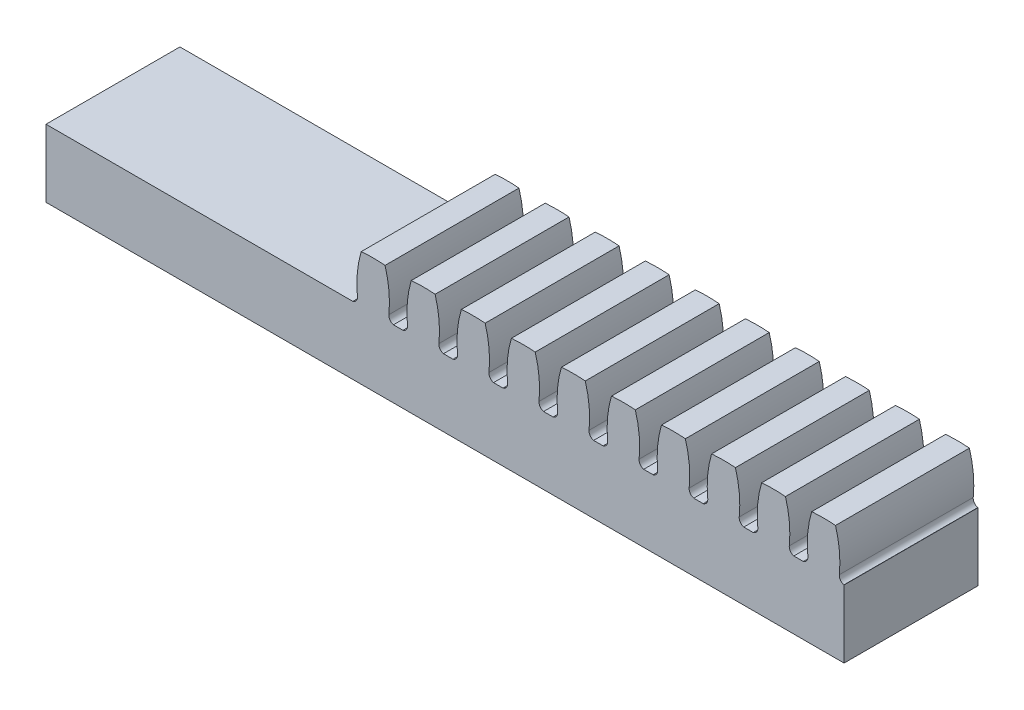
SolidWorks part; units mm, degrees
ref_plane "Front Plane" through (0, 0, 0) normal (0, 0, 1) x (1, 0, 0)
ref_plane "Top Plane" through (0, 0, 0) normal (0, 1, 0) x (1, 0, 0)
ref_plane "Right Plane" through (0, 0, 0) normal (1, 0, 0) x (0, 0, -1)
sketch "Sketch1" plane through (0, 0, 0) normal (0, 1, 0) x (1, 0, 0)
  line L1 (-29.5, 4.545) -> (29.5, 4.545)
  line L2 (-29.5, 4.545) -> (-29.5, -5.355)
  line L3 (-29.5, -5.355) -> (29.5, -5.355)
  line L4 (29.5, 4.545) -> (29.5, -5.355)
  dimension "D1" = 59
  dimension "D2" = 9.9
  dimension "D3" = 4.545
  dimension "D4" = 29.5
extrude "Boss-Extrude1" add sketch "Sketch1" along normal blind 5
sketch "Sketch7" plane through (0, 0, 5.355) normal (0, 0, 1) x (1, 0, 0)
  line L1 (26.47, 4.9959) -> (29.5, 4.9959)
  line L2 (7.97, 4.9959) -> (11, 4.9959)
  line L4 (22.77, 4.9959) -> (25.8, 4.9959)
  line L5 (19.07, 4.9959) -> (22.1, 4.9959)
  line L6 (15.37, 4.9959) -> (18.4, 4.9959)
  line L7 (11.67, 4.9959) -> (14.7, 4.9959)
  line L13 (4.27, 4.9959) -> (7.3, 4.9959)
  line L14 (0.57, 4.9959) -> (3.6, 4.9959)
  line L15 (-3.13, 4.9959) -> (-0.1, 4.9959)
  line L16 (-6.83, 4.9959) -> (-3.8, 4.9959)
  arc A0 (10.6481, 5.4819) -> (11, 4.9959) centre (11.0957, 5.4356) ccw
  arc A1 (7.97, 4.9959) -> (8.3219, 5.4819) centre (7.8743, 5.4356) ccw
  arc A2 (8.6039, 8.4968) -> (8.3219, 5.4819) centre (16.0413, 6.2805) ccw
  arc A3 (10.3661, 8.4968) -> (8.6039, 8.4968) centre (9.485, -1.9662) ccw
  arc A4 (10.6481, 5.4819) -> (10.3661, 8.4968) centre (2.9287, 6.2805) ccw
  arc A5 (29.1481, 5.4819) -> (29.5, 4.9959) centre (29.5957, 5.4356) ccw
  arc A6 (29.1481, 5.4819) -> (28.8661, 8.4968) centre (21.4287, 6.2805) ccw
  arc A7 (28.8661, 8.4968) -> (27.1039, 8.4968) centre (27.985, -1.9662) ccw
  arc A8 (27.1039, 8.4968) -> (26.8219, 5.4819) centre (34.5413, 6.2805) ccw
  arc A9 (26.47, 4.9959) -> (26.8219, 5.4819) centre (26.3743, 5.4356) ccw
  arc A15 (25.4481, 5.4819) -> (25.8, 4.9959) centre (25.8957, 5.4356) ccw
  arc A16 (22.77, 4.9959) -> (23.1219, 5.4819) centre (22.6743, 5.4356) ccw
  arc A17 (23.4039, 8.4968) -> (23.1219, 5.4819) centre (30.8413, 6.2805) ccw
  arc A18 (25.1661, 8.4968) -> (23.4039, 8.4968) centre (24.285, -1.9662) ccw
  arc A19 (25.4481, 5.4819) -> (25.1661, 8.4968) centre (17.7287, 6.2805) ccw
  arc A20 (21.7481, 5.4819) -> (22.1, 4.9959) centre (22.1957, 5.4356) ccw
  arc A21 (19.07, 4.9959) -> (19.4219, 5.4819) centre (18.9743, 5.4356) ccw
  arc A22 (19.7039, 8.4968) -> (19.4219, 5.4819) centre (27.1413, 6.2805) ccw
  arc A23 (21.4661, 8.4968) -> (19.7039, 8.4968) centre (20.585, -1.9662) ccw
  arc A24 (21.7481, 5.4819) -> (21.4661, 8.4968) centre (14.0287, 6.2805) ccw
  arc A25 (18.0481, 5.4819) -> (18.4, 4.9959) centre (18.4957, 5.4356) ccw
  arc A26 (15.37, 4.9959) -> (15.7219, 5.4819) centre (15.2743, 5.4356) ccw
  arc A27 (16.0039, 8.4968) -> (15.7219, 5.4819) centre (23.4413, 6.2805) ccw
  arc A28 (17.7661, 8.4968) -> (16.0039, 8.4968) centre (16.885, -1.9662) ccw
  arc A29 (18.0481, 5.4819) -> (17.7661, 8.4968) centre (10.3287, 6.2805) ccw
  arc A30 (14.3481, 5.4819) -> (14.7, 4.9959) centre (14.7957, 5.4356) ccw
  arc A31 (11.67, 4.9959) -> (12.0219, 5.4819) centre (11.5743, 5.4356) ccw
  arc A32 (12.3039, 8.4968) -> (12.0219, 5.4819) centre (19.7413, 6.2805) ccw
  arc A33 (14.0661, 8.4968) -> (12.3039, 8.4968) centre (13.185, -1.9662) ccw
  arc A34 (14.3481, 5.4819) -> (14.0661, 8.4968) centre (6.6287, 6.2805) ccw
  arc A60 (6.9481, 5.4819) -> (7.3, 4.9959) centre (7.3957, 5.4356) ccw
  arc A61 (4.27, 4.9959) -> (4.6219, 5.4819) centre (4.1743, 5.4356) ccw
  arc A62 (4.9039, 8.4968) -> (4.6219, 5.4819) centre (12.3413, 6.2805) ccw
  arc A63 (6.6661, 8.4968) -> (4.9039, 8.4968) centre (5.785, -1.9662) ccw
  arc A64 (6.9481, 5.4819) -> (6.6661, 8.4968) centre (-0.7713, 6.2805) ccw
  arc A65 (3.2481, 5.4819) -> (3.6, 4.9959) centre (3.6957, 5.4356) ccw
  arc A66 (0.57, 4.9959) -> (0.9219, 5.4819) centre (0.4743, 5.4356) ccw
  arc A67 (1.2039, 8.4968) -> (0.9219, 5.4819) centre (8.6413, 6.2805) ccw
  arc A68 (2.9661, 8.4968) -> (1.2039, 8.4968) centre (2.085, -1.9662) ccw
  arc A69 (3.2481, 5.4819) -> (2.9661, 8.4968) centre (-4.4713, 6.2805) ccw
  arc A70 (-0.4519, 5.4819) -> (-0.1, 4.9959) centre (-0.0043, 5.4356) ccw
  arc A71 (-3.13, 4.9959) -> (-2.7781, 5.4819) centre (-3.2257, 5.4356) ccw
  arc A72 (-2.4961, 8.4968) -> (-2.7781, 5.4819) centre (4.9413, 6.2805) ccw
  arc A73 (-0.7339, 8.4968) -> (-2.4961, 8.4968) centre (-1.615, -1.9662) ccw
  arc A74 (-0.4519, 5.4819) -> (-0.7339, 8.4968) centre (-8.1713, 6.2805) ccw
  arc A75 (-4.1519, 5.4819) -> (-3.8, 4.9959) centre (-3.7043, 5.4356) ccw
  arc A76 (-6.83, 4.9959) -> (-6.4781, 5.4819) centre (-6.9257, 5.4356) ccw
  arc A77 (-6.1961, 8.4968) -> (-6.4781, 5.4819) centre (1.2413, 6.2805) ccw
  arc A78 (-4.4339, 8.4968) -> (-6.1961, 8.4968) centre (-5.315, -1.9662) ccw
  arc A79 (-4.1519, 5.4819) -> (-4.4339, 8.4968) centre (-11.8713, 6.2805) ccw
  point P0 (0, 0)
  dimension "D1" = 0
  dimension "D2" = 10
extrude "Boss-Extrude4" add sketch "Sketch7" against normal through all
equation "\"module\"= 1.5"
equation "\"No of teeth\"= 12"
equation "\"D3@Sketch4\"=180 /  \"No of teeth\""
equation "\"D1@CirPattern1\"=\"No of teeth\""
equation "\"D1@Fillet1\"= .3 * \"module\""
